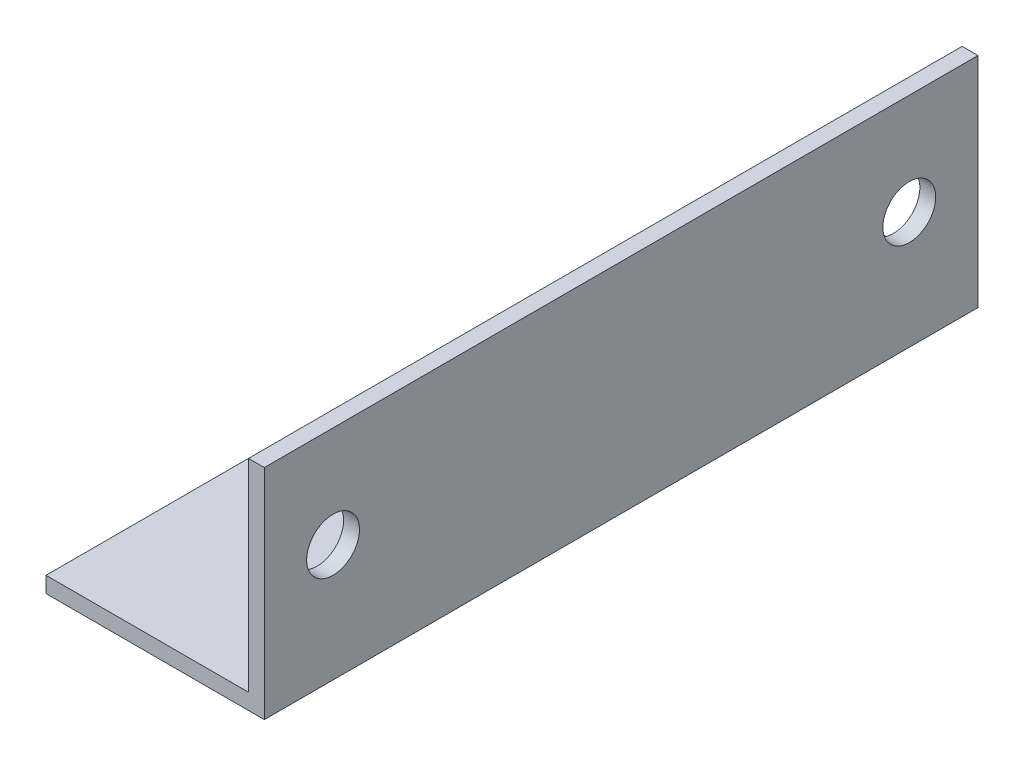
SolidWorks part; units mm, degrees
ref_plane "Plano frontal" through (0, 0, 0) normal (0, 0, 1) x (1, 0, 0)
ref_plane "Plano superior" through (0, 0, 0) normal (0, 1, 0) x (1, 0, 0)
ref_plane "Plano direito" through (0, 0, 0) normal (1, 0, 0) x (0, 0, -1)
sketch "Esboço1" plane through (0, 0, 0) normal (0, 0, 1) x (1, 0, 0)
  line L0 (0, 0) -> (16.52, 0)
  line L1 (16.52, 0) -> (16.52, 16.52)
  line L2 (16.52, 16.52) -> (15.32, 16.52)
  line L3 (15.32, 16.52) -> (15.32, 1.2)
  line L4 (15.32, 1.2) -> (0, 1.2)
  line L5 (0, 1.2) -> (0, 0)
  dimension "D1" = 16.52
  dimension "D2" = 16.52
  dimension "D3" = 1.2
  dimension "D4" = 1.2
extrude "Ressalto-extrusão1" add sketch "Esboço1" along normal blind 54
sketch "Esboço2" plane through (0, 0, 0) normal (1, 0, 0) x (0, 0, -1)
  line L0 (0, 16.52) -> (0, 1.2) construction
  line L1 (-54, 1.2) -> (0, 1.2) construction
  line L2 (-54, 16.52) -> (-54, 1.2) construction
  circle A0 centre (-5.2, 8.86) radius 2
  circle A1 centre (-48.8, 8.86) radius 2
  dimension "D4" = 4
  dimension "D5" = 4
  dimension "D1" = 5.2
  dimension "D2" = 7.66
  dimension "D3" = 5.2
extrude "Corte-extrusão1" cut sketch "Esboço2" along normal blind 14 from offset 10
